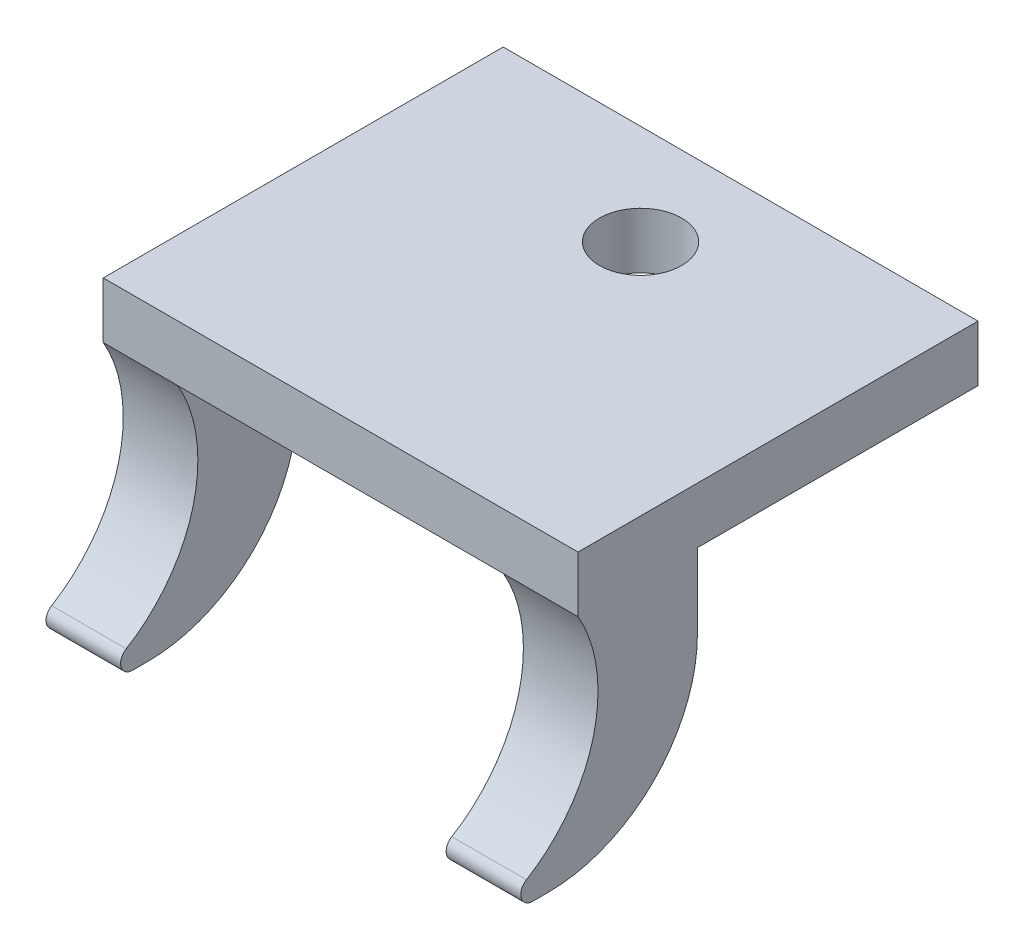
SolidWorks part; units mm, degrees
material "AISI 4340 Steel, annealed"
ref_plane "X-Y Datum" through (0, 0, 0) normal (0, 0, 1) x (1, 0, 0)
ref_plane "X-Z Datum" through (0, 0, 0) normal (0, 1, 0) x (1, 0, 0)
ref_plane "Y-Z Datum" through (0, 0, 0) normal (1, 0, 0) x (0, 0, -1)
sketch "Sketch1" plane through (0, 0, 0) normal (0, 1, 0) x (1, 0, 0)
  line L0 (20.2006, 32.3126) -> (20.2006, 15.2946) construction
  line L1 (0, 0) -> (40.4012, 0)
  line L2 (0, 0) -> (0, 34.036)
  line L3 (0, 34.036) -> (40.4012, 34.036)
  line L4 (40.4012, 0) -> (40.4012, 34.036)
  circle A0 centre (20.2006, 25.5224) radius 7.1006 construction
  circle A1 centre (20.2006, 25.5224) radius 1.2573
  dimension "D3" = 14.2011
  dimension "D4" = 8.5136
  dimension "D1" = 40.4012
  dimension "D2" = 34.036
extrude "Boss-Extrude1" add sketch "Sketch1" along normal blind 4.7625
hole_wizard "M6 Clearance Hole1" positions "Sketch3" profile "Sketch4" hole size "M6" standard "ANSI Metric" end condition through all
sketch "Sketch3" plane through (0, 4.7625, 0) normal (0, 1, 0) x (1, 0, 0)
  point P0 (20.2006, 25.5224)
sketch "Sketch4" plane through (20.2006, 4.7625, -25.5224) normal (1, 0, 0) x (0, 0, 1)
  line L0 (0, 0) -> (0, 4.7625)
  line L1 (0, 4.7625) -> (3.5, 4.7625)
  line L2 (3.5, 4.7625) -> (3.5, 0)
  line L5 (3.5, 0) -> (0, 0)
  line L11 (0, -6.35) -> (0, 107.95) construction
  dimension "Thru Hole Dia." = 7
  dimension "Thru Hole Depth" = 4.7625
sketch "Sketch5" plane through (40.4012, 0, 0) normal (1, 0, 0) x (0, 0, -1)
  line L5 (-10.9985, -19.05) -> (10.16, -19.05)
  line L8 (10.16, -19.05) -> (10.16, 0)
  line L14 (10.16, 0) -> (0, 0)
  line L16 (0, 0) -> (34.036, 0) construction
  arc A11 (-10.9985, -19.05) -> (0, 0) centre (-10.9985, -6.35) ccw
  point P7 (-14.515, 4.7625)
  dimension "D3" = 19.05
extrude "Boss-Extrude3" add sketch "Sketch5" against normal blind 6.35
ref_plane "Plane1" through (20.2006, 0, 0) normal (1, 0, 0) x (0, 0, -1)
mirror "Mirror1" about plane through (20.2006, 0, 0) normal (1, 0, 0) of "Boss-Extrude3"
sketch "Sketch7" [suppressed] plane through (40.4012, 0, 0) normal (1, 0, 0) x (0, 0, -1)
  line L0 (-5.5726, 4.7625) -> (-5.5726, 2.5739)
  arc A0 (-11.773, -20.6036) -> (-6.0928, 2.9085) centre (-12.7, -7.9375) ccw construction
  arc A1 (-5.5726, 4.7625) -> (-5.5726, 2.5739) centre (-5.5726, 3.6682) ccw
extrude "Cut-Extrude1" [suppressed] cut sketch "Sketch7" against normal through all
fillet "Fillet2" radius 1 2 edges at (3.175, -19.05, 10.9985) (37.2262, -19.05, 10.9985)
fillet "Fillet3" radius 12.7 2 edges at (3.175, -19.05, -10.16) (37.2262, -19.05, -10.16)
